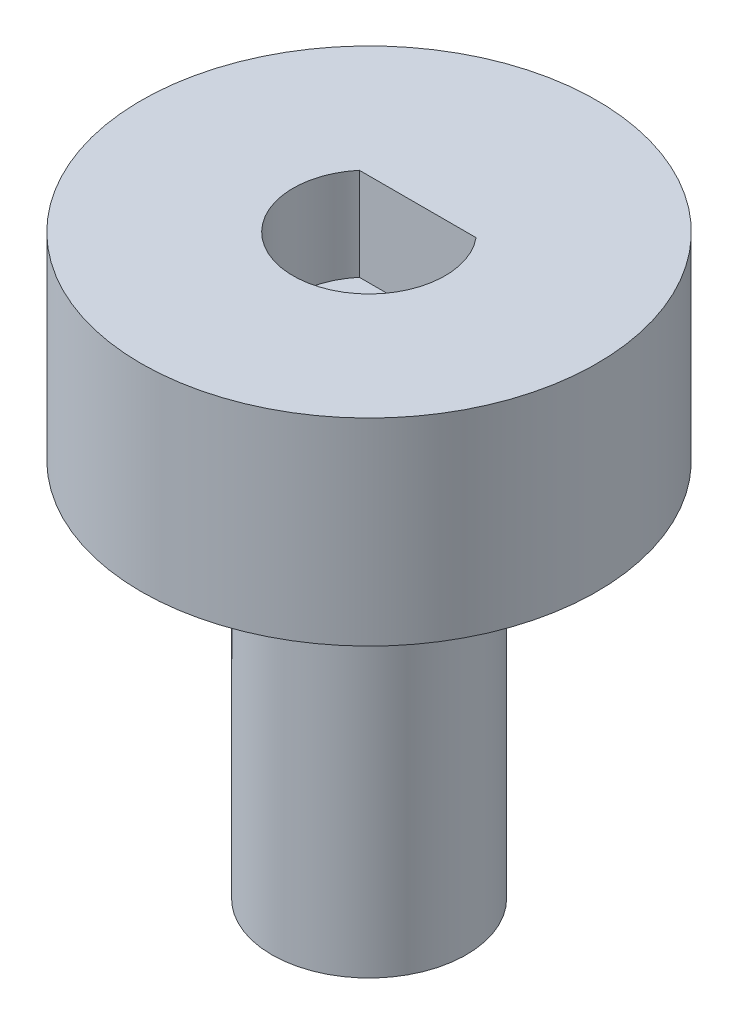
SolidWorks part; units mm, degrees
ref_plane "Front Plane" through (0, 0, 0) normal (0, 0, 1) x (1, 0, 0)
ref_plane "Top Plane" through (0, 0, 0) normal (0, 1, 0) x (1, 0, 0)
ref_plane "Right Plane" through (0, 0, 0) normal (1, 0, 0) x (0, 0, -1)
sketch "Sketch2" plane through (0, 0, 0) normal (0, 1, 0) x (1, 0, 0)
  circle A0 centre (0, 0) radius 4.066
  dimension "D1" = 8.132
extrude "Boss-Extrude1" add sketch "Sketch2" along normal blind 15.875
sketch "Sketch3" plane through (0, 15.875, 0) normal (0, 1, 0) x (1, 0, 0)
  circle A0 centre (0, 0) radius 9.525
  dimension "D1" = 19.05
extrude "Boss-Extrude2" add sketch "Sketch3" along normal blind 8.255
sketch "Sketch4" plane through (0, 24.13, 0) normal (0, 1, 0) x (1, 0, 0)
  line L0 (-2.4396, 2.032) -> (2.4396, 2.032)
  arc A0 (-2.4396, 2.032) -> (2.4396, 2.032) centre (0, 0) ccw
  dimension "D1" = 6.35
extrude "Cut-Extrude1" cut sketch "Sketch4" against normal blind 3.875
